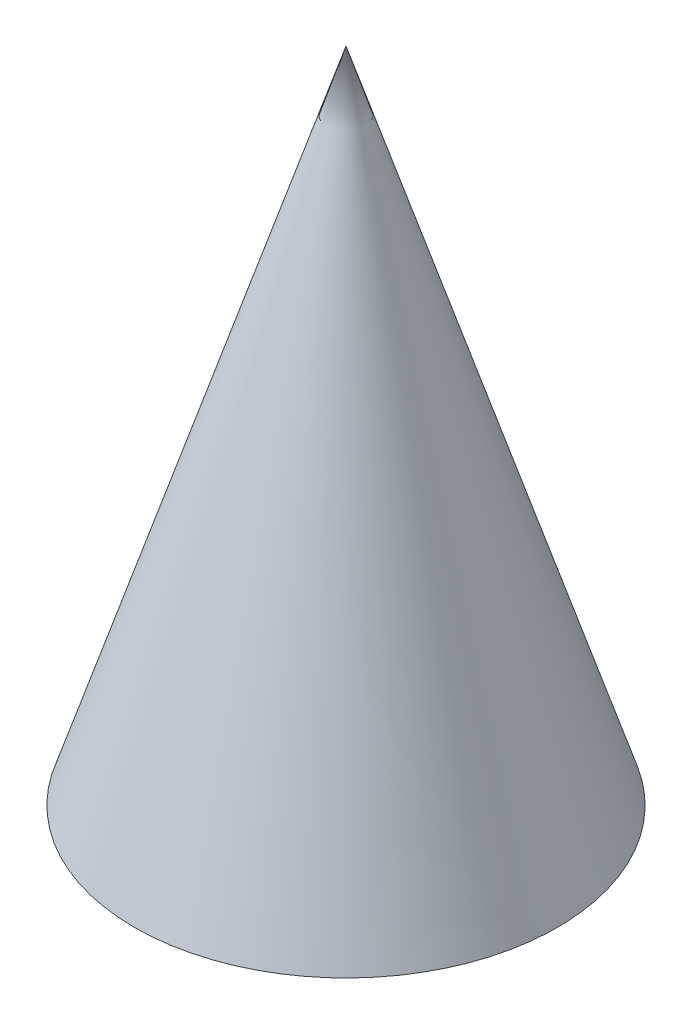
SolidWorks part; units mm, degrees
material "Pine"
ref_plane "Front Plane" through (0, 0, 0) normal (0, 0, 1) x (1, 0, 0)
ref_plane "Top Plane" through (0, 0, 0) normal (0, 1, 0) x (1, 0, 0)
ref_plane "Right Plane" through (0, 0, 0) normal (1, 0, 0) x (0, 0, -1)
sketch "Sketch1" plane through (0, 0, 0) normal (0, 1, 0) x (1, 0, 0)
  circle A0 centre (0, 0) radius 24.511
  dimension "D1" = 49.022
ref_plane "Plane1" through (0, 76.2, 0) normal (0, 1, 0) x (1, 0, 0)
sketch "Sketch2" plane through (0, 76.2, 0) normal (0, 1, 0) x (1, 0, 0)
  point P0 (0, 0)
loft "Loft2" add profiles "Sketch1", "Sketch2"
